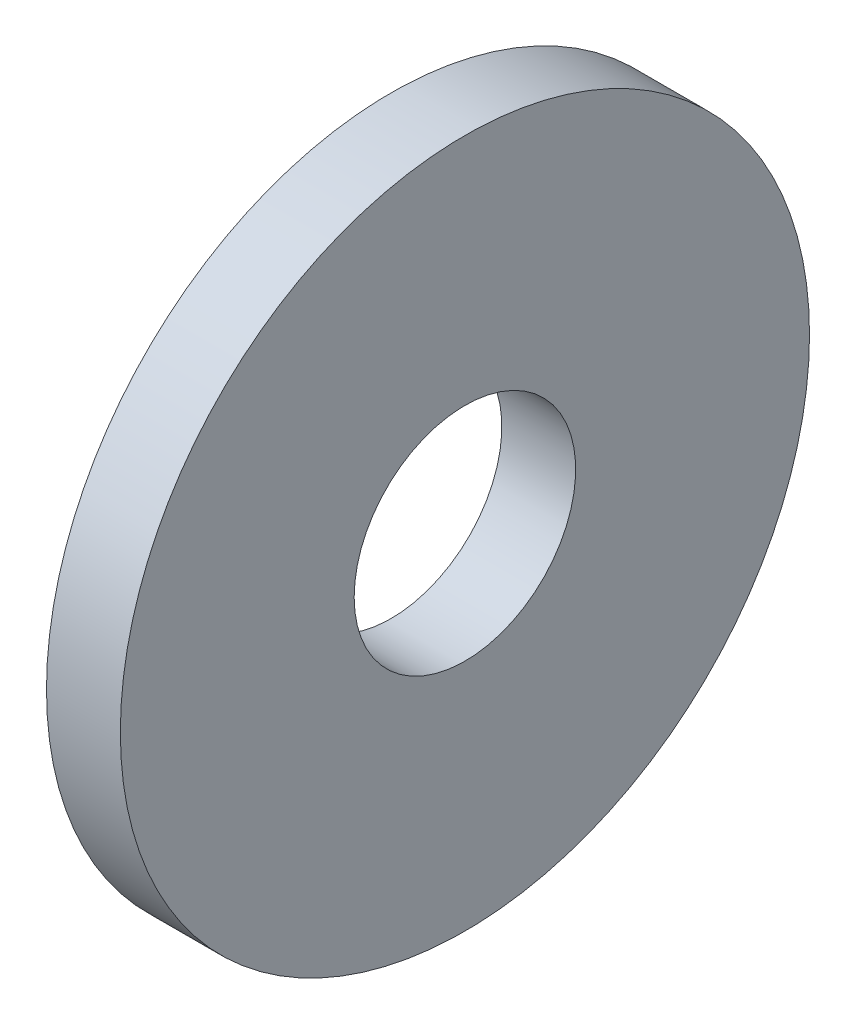
SolidWorks part; units mm, degrees
ref_plane "Plane1" through (0, 0, 0) normal (0, 0, 1) x (1, 0, 0)
ref_plane "Plane2" through (0, 0, 0) normal (0, 1, 0) x (1, 0, 0)
ref_plane "Plane3" through (0, 0, 0) normal (1, 0, 0) x (0, 0, -1)
sketch "Sketch1" plane through (0, 0, 0) normal (0, 0, 1) x (1, 0, 0)
  line L0 (-34.925, 0) -> (9.525, 0) construction
  line L1 (0, 4.5) -> (0, 14)
  line L2 (0, 14) -> (-3, 14)
  line L3 (-3, 14) -> (-3, 4.5)
  line L4 (-3, 4.5) -> (0, 4.5)
  dimension "Thickness" = 3
  dimension "Inside_dia" = 9
  dimension "Outside_dia" = 28
revolve "Base-Revolve" add sketch "Sketch1" angle 360 about L0
